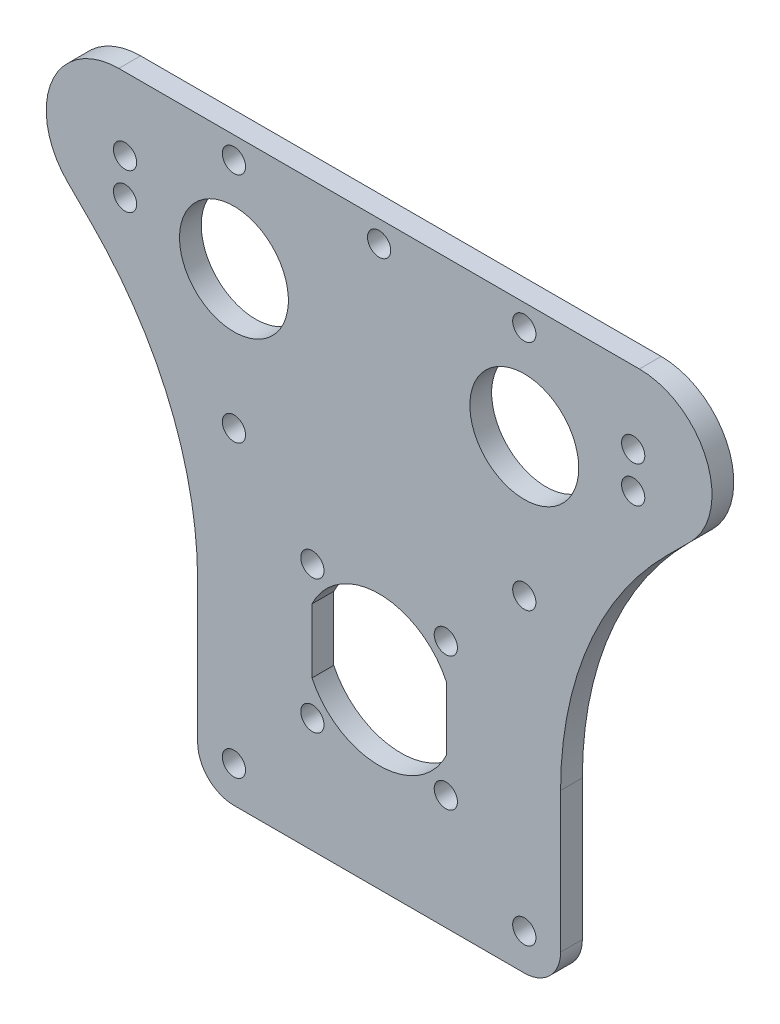
SolidWorks part; units mm, degrees
ref_plane "正面" through (0, 0, 0) normal (0, 0, 1) x (1, 0, 0)
ref_plane "平面" through (0, 0, 0) normal (0, 1, 0) x (1, 0, 0)
ref_plane "右側面" through (0, 0, 0) normal (1, 0, 0) x (0, 0, -1)
sketch "ｽｹｯﾁ1" plane through (0, 0, 0) normal (0, 0, 1) x (1, 0, 0)
  line L1 (-20, 20) -> (20, 20) construction
  line L2 (-20, 20) -> (-20, -20) construction
  line L3 (-20, -20) -> (20, -20) construction
  line L4 (20, 20) -> (20, -20) construction
  line L5 (-20, 20) -> (20, -20) construction
  line L6 (-20, -20) -> (20, 20) construction
  line L7 (-9.1924, 9.1924) -> (9.1924, 9.1924) construction
  line L8 (-9.1924, 9.1924) -> (-9.1924, -9.1924) construction
  line L9 (-9.1924, -9.1924) -> (9.1924, -9.1924) construction
  line L10 (9.1924, 9.1924) -> (9.1924, -9.1924) construction
  line L11 (-9.1924, 9.1924) -> (9.1924, -9.1924) construction
  line L12 (-9.1924, -9.1924) -> (9.1924, 9.1924) construction
  line L13 (-25, 25) -> (25, 25)
  line L14 (-25, 25) -> (-25, -25)
  line L15 (-25, -25) -> (25, -25)
  line L16 (25, 25) -> (25, -25)
  line L17 (-25, 25) -> (25, -25) construction
  line L18 (-25, -25) -> (25, 25) construction
  circle A0 centre (-20, 20) radius 1.6
  circle A1 centre (-9.1924, 9.1924) radius 1.6
  circle A2 centre (9.1924, 9.1924) radius 1.6
  circle A3 centre (20, 20) radius 1.6
  circle A4 centre (9.1924, -9.1924) radius 1.6
  circle A5 centre (20, -20) radius 1.6
  circle A6 centre (-9.1924, -9.1924) radius 1.6
  circle A7 centre (-20, -20) radius 1.6
  point P0 (0, 0)
  point P5 (0, 0)
  point P10 (0, 0)
  dimension "D3" = 4
  dimension "D4" = 3.2
  dimension "D1" = 40
  dimension "D2" = 13
  dimension "D5" = 50
extrude "ﾎﾞｽ - 押し出し1" add sketch "ｽｹｯﾁ1" along normal blind 3
fillet "ﾌｨﾚｯﾄ1" radius 5 4 edges at (25, -25, 1.5) (-25, -25, 1.5) (-25, 25, 1.5) (25, 25, 1.5)
sketch "ｽｹｯﾁ2" plane through (0, 0, 3) normal (0, 0, 1) x (1, 0, 0)
  line L0 (-9.25, 4.4159) -> (-9.25, -4.4159)
  line L2 (9.25, -4.4159) -> (9.25, 4.4159)
  arc A0 (-9.25, -4.4159) -> (9.25, -4.4159) centre (0, 0) ccw
  arc A1 (9.25, 4.4159) -> (-9.25, 4.4159) centre (0, 0) ccw
  dimension "D1" = 18.5
  dimension "D2" = 20.5
extrude "ｶｯﾄ - 押し出し1" cut sketch "ｽｹｯﾁ2" against normal through all
sketch "ｽｹｯﾁ3" plane through (0, 0, 3) normal (0, 0, 1) x (1, 0, 0)
  line L0 (-25, 20) -> (-42.9289, 37.9289)
  line L1 (-35.8579, 55) -> (35.8579, 55)
  line L2 (42.9289, 37.9289) -> (25, 20)
  line L3 (25, -20) -> (25, 20) construction
  line L4 (-25, 20) -> (-25, -20) construction
  line L5 (20, 25) -> (-20, 25) construction
  line L10 (-20, -25) -> (20, -25)
  line L11 (25, -20) -> (25, 20)
  line L12 (20, 25) -> (-20, 25)
  line L13 (-25, 20) -> (-25, -20)
  line L16 (20, 25) -> (-20, 25)
  arc A0 (35.8579, 55) -> (42.9289, 37.9289) centre (35.8579, 45) cw
  arc A1 (-42.9289, 37.9289) -> (-35.8579, 55) centre (-35.8579, 45) cw
  arc A6 (20, -25) -> (25, -20) centre (20, -20) ccw
  arc A7 (25, 20) -> (20, 25) centre (20, 20) ccw
  arc A8 (-20, 25) -> (-25, 20) centre (-20, 20) ccw
  arc A9 (-25, -20) -> (-20, -25) centre (-20, -20) ccw
  arc A11 (25, 20) -> (20, 25) centre (20, 20) ccw
  arc A12 (-20, 25) -> (-25, 20) centre (-20, 20) ccw
  dimension "D4" = 10
  dimension "D1" = 135
  dimension "D2" = 135
  dimension "D3" = 30
  dimension "D5" = 0
extrude "ﾎﾞｽ - 押し出し2" add sketch "ｽｹｯﾁ3" against normal through all
fillet "ﾌｨﾚｯﾄ2" radius 50 2 edges at (-25, 20, 1.5) (25, 20, 1.5)
sketch "ｽｹｯﾁ4" plane through (0, 0, 3) normal (0, 0, 1) x (1, 0, 0)
  line L0 (-50, 45) -> (50, 45) construction
  line L1 (-42.9289, 37.9289) -> (-39.6447, 34.6447) construction
  line L2 (39.6447, 34.6447) -> (42.9289, 37.9289) construction
  line L3 (35.8579, 55) -> (-35.8579, 55) construction
  line L4 (0, 0) -> (0, 45) construction
  circle A0 centre (-35, 45) radius 1.6
  circle A1 centre (35, 45) radius 1.6
  dimension "D2" = 35
  dimension "D3" = 3.2
  dimension "D1" = 10
extrude "ｶｯﾄ - 押し出し2" cut sketch "ｽｹｯﾁ4" against normal through all
sketch "ｽｹｯﾁ5" plane through (0, 0, 3) normal (0, 0, 1) x (1, 0, 0)
  line L0 (0, 0) -> (0, 55) construction
  line L1 (35.8579, 55) -> (-35.8579, 55) construction
  circle A0 centre (20, 39) radius 7.5
  circle A1 centre (-20, 39) radius 7.5
  dimension "D1" = 15
  dimension "D2" = 16
  dimension "D3" = 20
extrude "ｶｯﾄ - 押し出し3" cut sketch "ｽｹｯﾁ5" against normal through all
sketch "ｽｹｯﾁ6" plane through (0, 0, 0) normal (0, 0, -1) x (-1, 0, 0)
  line L0 (-35, 45) -> (-35, 40) construction
  line L1 (0, 0) -> (0, 55) construction
  line L2 (-35.8579, 55) -> (35.8579, 55) construction
  circle A0 centre (-35, 40) radius 1.6
  circle A1 centre (35, 40) radius 1.6
  dimension "D1" = 5
  dimension "D2" = 3.2
extrude "ｶｯﾄ - 押し出し4" cut sketch "ｽｹｯﾁ6" against normal through all
sketch "ｽｹｯﾁ7" plane through (0, 0, 3) normal (0, 0, 1) x (1, 0, 0)
  line L0 (0, 52) -> (0, 55) construction
  line L1 (35.8579, 55) -> (-35.8579, 55) construction
  circle A0 centre (0, 52) radius 1.6
  circle A1 centre (20, 52) radius 1.6
  circle A2 centre (-20, 52) radius 1.6
  point P8 (-30.9758, 50)
  dimension "D1" = 3.2
  dimension "D2" = 3
  dimension "D5" = 20
  dimension "D6" = 20
  dimension "D3" = 2
  dimension "D4" = 2
extrude "ｶｯﾄ - 押し出し5" cut sketch "ｽｹｯﾁ7" against normal through all
